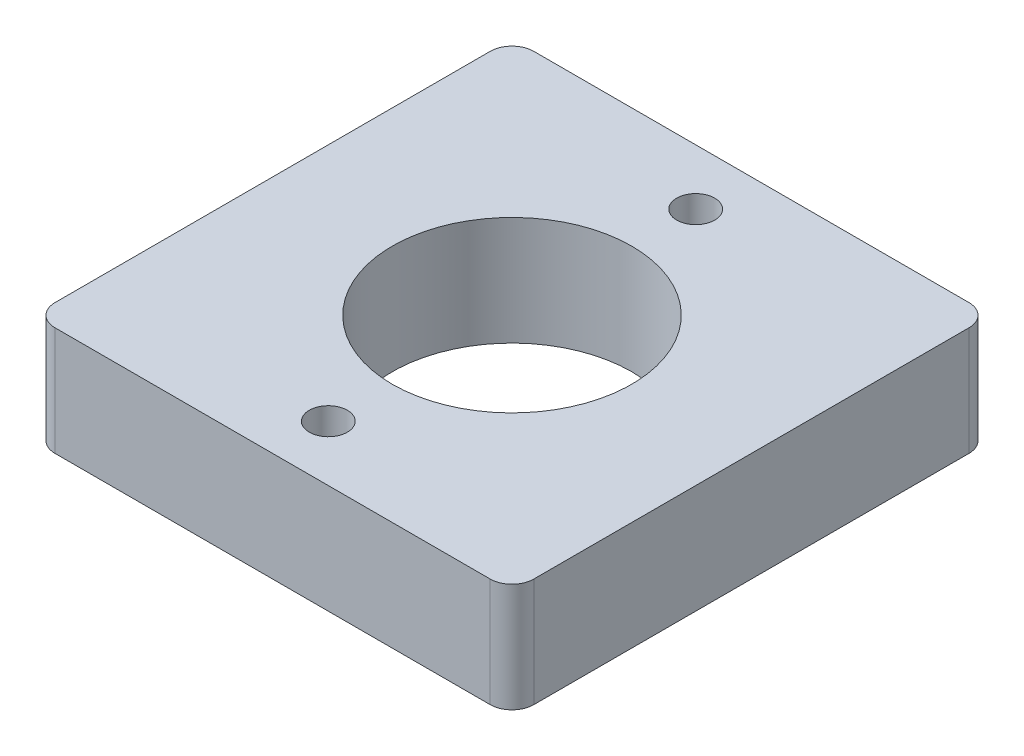
SolidWorks part; units mm, degrees
ref_plane "Alzado" through (0, 0, 0) normal (0, 0, 1) x (1, 0, 0)
ref_plane "Planta" through (0, 0, 0) normal (0, 1, 0) x (1, 0, 0)
ref_plane "Vista lateral" through (0, 0, 0) normal (1, 0, 0) x (0, 0, -1)
sketch "Croquis1" plane through (0, 0, 0) normal (0, 1, 0) x (1, 0, 0)
  line L1 (-22, -22) -> (22, -22)
  line L2 (-22, -22) -> (-22, 22)
  line L3 (-22, 22) -> (22, 22)
  line L4 (22, -22) -> (22, 22)
  line L5 (-22, -22) -> (22, 22) construction
  line L6 (-22, 22) -> (22, -22) construction
  circle A0 centre (0, 0) radius 11
  point P0 (0, 0)
  dimension "D3" = 22
  dimension "D1" = 44
  dimension "D2" = 44
extrude "Saliente-Extruir1" add sketch "Croquis1" along normal blind 10
sketch "Croquis2" plane through (0, 10, 0) normal (0, 1, 0) x (1, 0, 0)
  line L0 (-22, 22) -> (-22, -22) construction
  line L1 (22, -11.75) -> (-22, -11.75) construction
  line L2 (22, -11.75) -> (22, 11.75) construction
  line L3 (22, 11.75) -> (-22, 11.75) construction
  line L4 (-22, -11.75) -> (-22, 11.75) construction
  line L5 (22, -11.75) -> (-22, 11.75) construction
  line L6 (22, 11.75) -> (-22, -11.75) construction
  line L7 (-22, 16.88) -> (22, 16.88) construction
  line L8 (22, -22) -> (22, 22) construction
  line L9 (0, 22) -> (0, -22) construction
  line L10 (22, 22) -> (-22, 22) construction
  line L11 (-22, -22) -> (22, -22) construction
  line L12 (-22, -16.88) -> (22, -16.88) construction
  circle A0 centre (0, 16.88) radius 1.75
  circle A1 centre (0, -16.88) radius 1.75
  point P0 (0, 0)
  point P18 (0, 16.88)
  point P19 (0, -16.88)
  dimension "D4" = 3.5
  dimension "D5" = 3.5
  dimension "D1" = 23.5
  dimension "D2" = 5.13
  dimension "D3" = 5.13
extrude "Cortar-Extruir1" cut sketch "Croquis2" against normal through all
fillet "Redondeo1" radius 2 4 edges at (22, 5, -22) (22, 5, 22) (-22, 5, 22) (-22, 5, -22)
